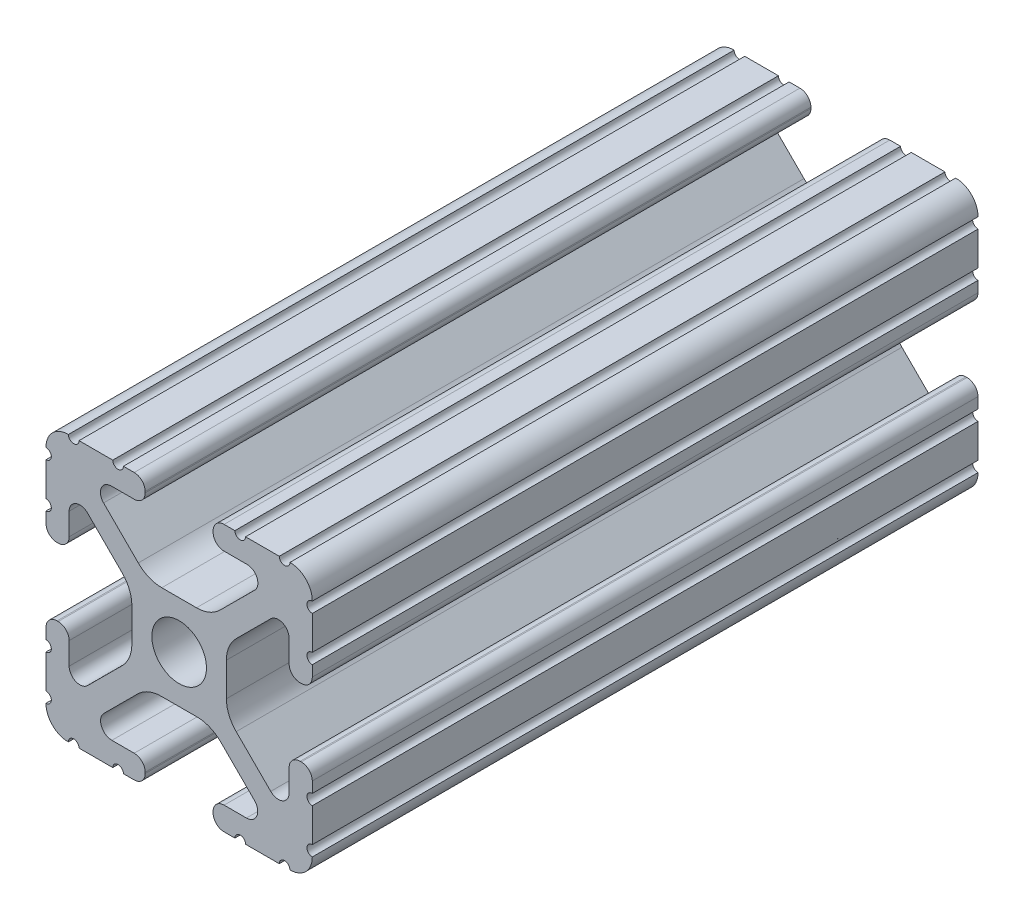
SolidWorks part; units mm, degrees
material "6105-T5 Aluminum"
ref_plane "Front Plane" through (0, 0, 0) normal (0, 0, 1) x (1, 0, 0)
ref_plane "Top Plane" through (0, 0, 0) normal (0, 1, 0) x (1, 0, 0)
ref_plane "Right Plane" through (0, 0, 0) normal (1, 0, 0) x (0, 0, -1)
sketch "Sketch1" plane through (0, 0, 0) normal (0, 0, 1) x (1, 0, 0)
  line L0 (-7.207, 8.7244) -> (-3.8983, 5.4232)
  line L1 (-4.2875, 10.4902) -> (-6.4768, 10.4902)
  line L2 (-3.2385, 11.651) -> (-3.2385, 11.5392)
  line L3 (-5.3171, 12.7) -> (-4.2875, 12.7)
  line L4 (0, 13.4005) -> (0, -14.8534) construction
  line L5 (12.7, 0) -> (-13.9989, 0) construction
  line L6 (-9.5504, 12.7) -> (-6.3331, 12.7)
  line L7 (-12.7, 6.3331) -> (-12.7, 9.5504)
  line L8 (-12.7, 4.2875) -> (-12.7, 5.3171)
  line L9 (-11.5392, 3.2385) -> (-11.651, 3.2385)
  line L10 (-10.4902, 6.4021) -> (-10.4902, 4.2875)
  line L11 (-5.441, 3.8408) -> (-8.7371, 7.1294)
  line L12 (-4.5085, -1.5932) -> (-4.5085, 1.5932)
  line L13 (-1.7093, -4.4958) -> (1.7093, -4.4958)
  line L14 (3.9523, -5.4237) -> (7.1797, -8.6452)
  line L15 (6.4164, -10.4902) -> (4.2875, -10.4902)
  line L16 (3.2385, -11.5392) -> (3.2385, -11.651)
  line L17 (4.2875, -12.7) -> (5.3171, -12.7)
  line L18 (6.3331, -12.7) -> (9.5504, -12.7)
  line L19 (12.7, -9.5504) -> (12.7, -6.3331)
  line L20 (12.7, -5.3171) -> (12.7, -4.2875)
  line L21 (11.651, -3.2385) -> (11.5392, -3.2385)
  line L22 (10.4902, -4.2875) -> (10.4902, -6.4021)
  line L23 (8.7371, -7.1294) -> (5.441, -3.8408)
  line L24 (4.5085, -1.5932) -> (4.5085, 1.5932)
  line L25 (5.441, 3.8408) -> (8.7371, 7.1294)
  line L26 (10.4902, 6.4021) -> (10.4902, 4.2875)
  line L27 (11.5392, 3.2385) -> (11.651, 3.2385)
  line L28 (12.7, 4.2875) -> (12.7, 5.3171)
  line L29 (12.7, 6.3331) -> (12.7, 9.5504)
  line L30 (9.5504, 12.7) -> (6.3331, 12.7)
  line L31 (5.3171, 12.7) -> (4.2875, 12.7)
  line L32 (3.2385, 11.651) -> (3.2385, 11.5392)
  line L33 (4.2875, 10.4902) -> (6.4768, 10.4902)
  line L34 (7.207, 8.7244) -> (3.8983, 5.4232)
  line L35 (1.6558, 4.4958) -> (-1.6558, 4.4958)
  line L36 (-8.7371, -7.1294) -> (-5.441, -3.8408)
  line L37 (-10.4902, -4.2875) -> (-10.4902, -6.4021)
  line L38 (-11.651, -3.2385) -> (-11.5392, -3.2385)
  line L39 (-12.7, -5.3171) -> (-12.7, -4.2875)
  line L40 (-12.7, -9.5504) -> (-12.7, -6.3331)
  line L41 (-6.3331, -12.7) -> (-9.5504, -12.7)
  line L42 (-4.2875, -12.7) -> (-5.3171, -12.7)
  line L43 (-3.2385, -11.5392) -> (-3.2385, -11.651)
  line L44 (-6.4164, -10.4902) -> (-4.2875, -10.4902)
  line L45 (-3.9523, -5.4237) -> (-7.1797, -8.6452)
  arc A0 (-7.207, 8.7244) -> (-6.4768, 10.4902) centre (-6.4768, 9.4563) cw
  arc A1 (-3.2385, 11.5392) -> (-4.2875, 10.4902) centre (-4.2875, 11.5392) cw
  arc A2 (-4.2875, 12.7) -> (-3.2385, 11.651) centre (-4.2875, 11.651) cw
  arc A3 (-5.3171, 12.7) -> (-6.3331, 12.7) centre (-5.8251, 12.7) cw
  arc A4 (-9.5504, 12.7) -> (-10.5664, 12.6998) centre (-10.0584, 12.7) cw
  arc A5 (-12.6998, 10.5664) -> (-10.5664, 12.6998) centre (-10.5918, 10.5918) cw
  arc A6 (-12.6998, 10.5664) -> (-12.7, 9.5504) centre (-12.7, 10.0584) cw
  arc A7 (-12.7, 6.3331) -> (-12.7, 5.3171) centre (-12.7, 5.8251) cw
  arc A8 (-11.651, 3.2385) -> (-12.7, 4.2875) centre (-11.651, 4.2875) cw
  arc A9 (-10.4902, 4.2875) -> (-11.5392, 3.2385) centre (-11.5392, 4.2875) cw
  circle A10 centre (0, 0) radius 2.6035
  arc A11 (-10.4902, 6.4021) -> (-8.7371, 7.1294) centre (-9.4628, 6.4021) cw
  arc A12 (-5.441, 3.8408) -> (-4.5085, 1.5932) centre (-7.6835, 1.5932) cw
  arc A13 (-4.5085, -1.5932) -> (-5.441, -3.8408) centre (-7.6835, -1.5932) cw
  arc A14 (-8.7371, -7.1294) -> (-10.4902, -6.4021) centre (-9.4628, -6.4021) cw
  arc A15 (-1.7093, -4.4958) -> (-3.9523, -5.4237) centre (-1.7093, -7.6708) ccw
  arc A16 (3.9523, -5.4237) -> (1.7093, -4.4958) centre (1.7093, -7.6708) ccw
  arc A17 (6.4164, -10.4902) -> (7.1797, -8.6452) centre (6.4164, -9.4098) ccw
  arc A18 (4.2875, -10.4902) -> (3.2385, -11.5392) centre (4.2875, -11.5392) ccw
  arc A19 (3.2385, -11.651) -> (4.2875, -12.7) centre (4.2875, -11.651) ccw
  arc A20 (6.3331, -12.7) -> (5.3171, -12.7) centre (5.8251, -12.7) ccw
  arc A21 (10.5664, -12.6998) -> (9.5504, -12.7) centre (10.0584, -12.7) ccw
  arc A22 (10.5664, -12.6998) -> (12.6998, -10.5664) centre (10.5918, -10.5918) ccw
  arc A23 (12.7, -9.5504) -> (12.6998, -10.5664) centre (12.7, -10.0584) ccw
  arc A24 (12.7, -5.3171) -> (12.7, -6.3331) centre (12.7, -5.8251) ccw
  arc A25 (12.7, -4.2875) -> (11.651, -3.2385) centre (11.651, -4.2875) ccw
  arc A26 (11.5392, -3.2385) -> (10.4902, -4.2875) centre (11.5392, -4.2875) ccw
  arc A27 (8.7371, -7.1294) -> (10.4902, -6.4021) centre (9.4628, -6.4021) ccw
  arc A28 (4.5085, -1.5932) -> (5.441, -3.8408) centre (7.6835, -1.5932) ccw
  arc A29 (5.441, 3.8408) -> (4.5085, 1.5932) centre (7.6835, 1.5932) ccw
  arc A30 (10.4902, 6.4021) -> (8.7371, 7.1294) centre (9.4628, 6.4021) ccw
  arc A31 (10.4902, 4.2875) -> (11.5392, 3.2385) centre (11.5392, 4.2875) ccw
  arc A32 (11.651, 3.2385) -> (12.7, 4.2875) centre (11.651, 4.2875) ccw
  arc A33 (12.7, 6.3331) -> (12.7, 5.3171) centre (12.7, 5.8251) ccw
  arc A34 (12.6998, 10.5664) -> (12.7, 9.5504) centre (12.7, 10.0584) ccw
  arc A35 (12.6998, 10.5664) -> (10.5664, 12.6998) centre (10.5918, 10.5918) ccw
  arc A36 (9.5504, 12.7) -> (10.5664, 12.6998) centre (10.0584, 12.7) ccw
  arc A37 (5.3171, 12.7) -> (6.3331, 12.7) centre (5.8251, 12.7) ccw
  arc A38 (4.2875, 12.7) -> (3.2385, 11.651) centre (4.2875, 11.651) ccw
  arc A39 (3.2385, 11.5392) -> (4.2875, 10.4902) centre (4.2875, 11.5392) ccw
  arc A40 (7.207, 8.7244) -> (6.4768, 10.4902) centre (6.4768, 9.4563) ccw
  arc A41 (1.6558, 4.4958) -> (3.8983, 5.4232) centre (1.6558, 7.6708) ccw
  arc A42 (-1.6558, 4.4958) -> (-3.8983, 5.4232) centre (-1.6558, 7.6708) cw
  arc A43 (-11.5392, -3.2385) -> (-10.4902, -4.2875) centre (-11.5392, -4.2875) cw
  arc A44 (-12.7, -4.2875) -> (-11.651, -3.2385) centre (-11.651, -4.2875) cw
  arc A45 (-12.7, -5.3171) -> (-12.7, -6.3331) centre (-12.7, -5.8251) cw
  arc A46 (-12.7, -9.5504) -> (-12.6998, -10.5664) centre (-12.7, -10.0584) cw
  arc A47 (-10.5664, -12.6998) -> (-12.6998, -10.5664) centre (-10.5918, -10.5918) cw
  arc A48 (-10.5664, -12.6998) -> (-9.5504, -12.7) centre (-10.0584, -12.7) cw
  arc A49 (-6.3331, -12.7) -> (-5.3171, -12.7) centre (-5.8251, -12.7) cw
  arc A50 (-3.2385, -11.651) -> (-4.2875, -12.7) centre (-4.2875, -11.651) cw
  arc A51 (-4.2875, -10.4902) -> (-3.2385, -11.5392) centre (-4.2875, -11.5392) cw
  arc A52 (-6.4164, -10.4902) -> (-7.1797, -8.6452) centre (-6.4164, -9.4098) cw
  dimension "D1" = 5.207
  dimension "D9" = 14.859
  dimension "D2" = 25.4
  dimension "D3" = 12.7
  dimension "D4" = 6.477
  dimension "D5" = 8.2042
  dimension "D6" = 9.017
  dimension "D8" = 2.2098
  dimension "D10" = 2.2098
extrude "Extrude1" add sketch "Sketch1" against normal blind 63.5
